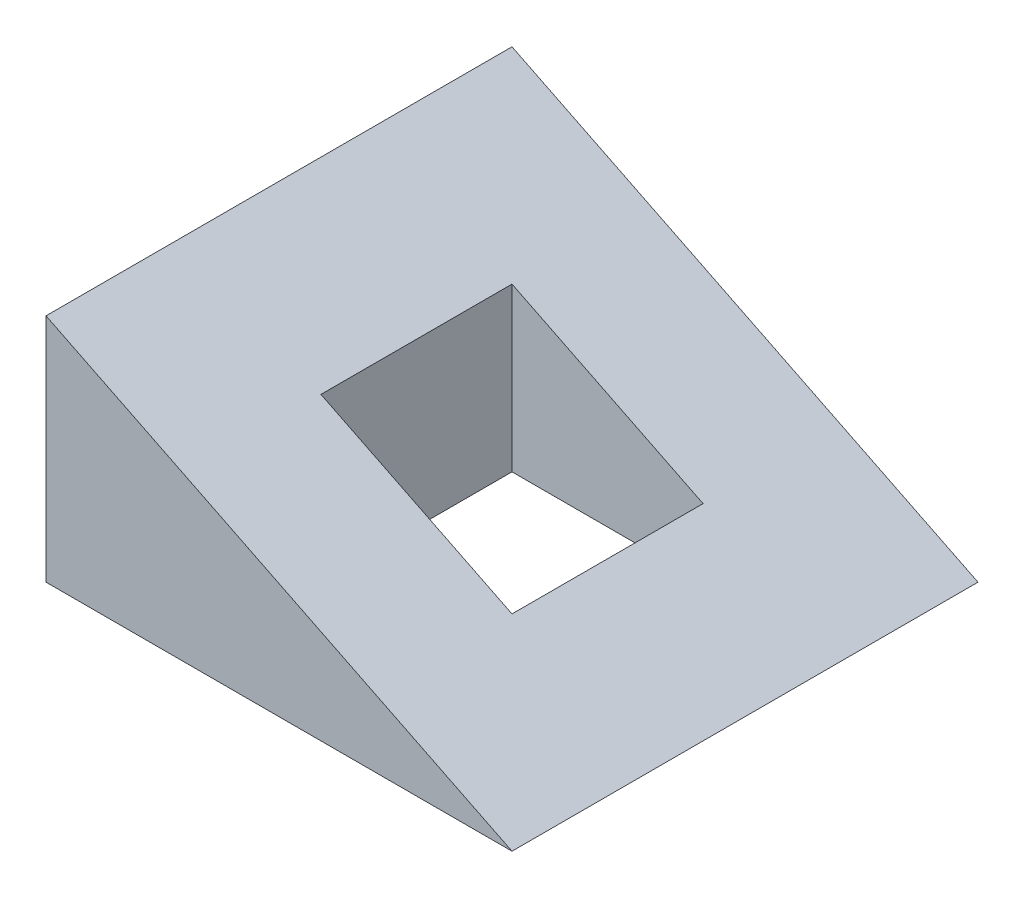
SolidWorks part; units mm, degrees
ref_plane "Front Plane" through (0, 0, 0) normal (0, 0, 1) x (1, 0, 0)
ref_plane "Top Plane" through (0, 0, 0) normal (0, 1, 0) x (1, 0, 0)
ref_plane "Right Plane" through (0, 0, 0) normal (1, 0, 0) x (0, 0, -1)
sketch "Croquis1" plane through (0, 0, 0) normal (0, 0, 1) x (1, 0, 0)
  line L0 (0, 0) -> (20, 0)
  line L1 (20, 0) -> (0, 9.9)
  line L2 (0, 9.9) -> (0, 0)
  dimension "D1" = 9.9
  dimension "D2" = 20
extrude "Saliente-Extruir1" add sketch "Croquis1" along normal blind 20
sketch "Croquis2" plane through (0, 0, 0) normal (0, -1, 0) x (1, 0, 0)
  line L0 (0, 0) -> (20, 20) construction
  line L1 (20, 0) -> (0, 20) construction
  line L3 (5.9, 5.9) -> (14.1, 5.9)
  line L4 (5.9, 5.9) -> (5.9, 14.1)
  line L5 (5.9, 14.1) -> (14.1, 14.1)
  line L6 (14.1, 5.9) -> (14.1, 14.1)
  line L7 (5.9, 5.9) -> (14.1, 14.1) construction
  line L8 (5.9, 14.1) -> (14.1, 5.9) construction
  point P8 (10, 10)
  dimension "D1" = 8.2
extrude "Cortar-Extruir1" cut sketch "Croquis2" against normal blind 20
